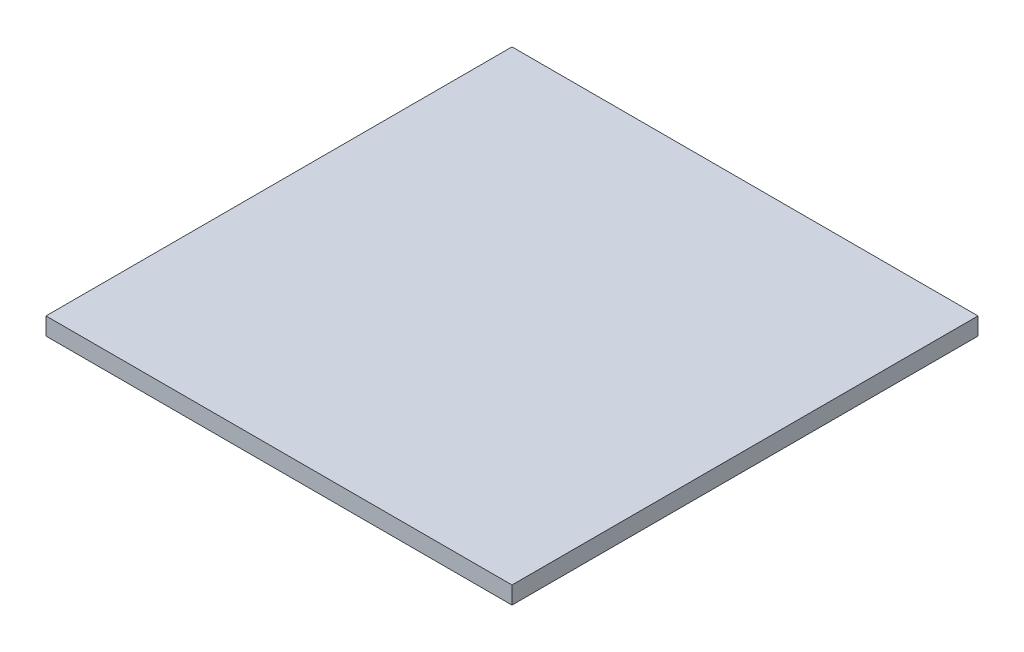
SolidWorks part; units mm, degrees
ref_plane "Спереди" through (0, 0, 0) normal (0, 0, 1) x (1, 0, 0)
ref_plane "Сверху" through (0, 0, 0) normal (0, 1, 0) x (1, 0, 0)
ref_plane "Справа" through (0, 0, 0) normal (1, 0, 0) x (0, 0, -1)
sketch "Эскиз1" plane through (0, 0, 0) normal (0, 1, 0) x (1, 0, 0)
  line L1 (0, 0) -> (400, 0)
  line L2 (0, 0) -> (0, 400)
  line L3 (0, 400) -> (400, 400)
  line L4 (400, 0) -> (400, 400)
  dimension "D1" = 400
  dimension "D2" = 400
extrude "Бобышка-Вытянуть1" add sketch "Эскиз1" along normal blind 15
